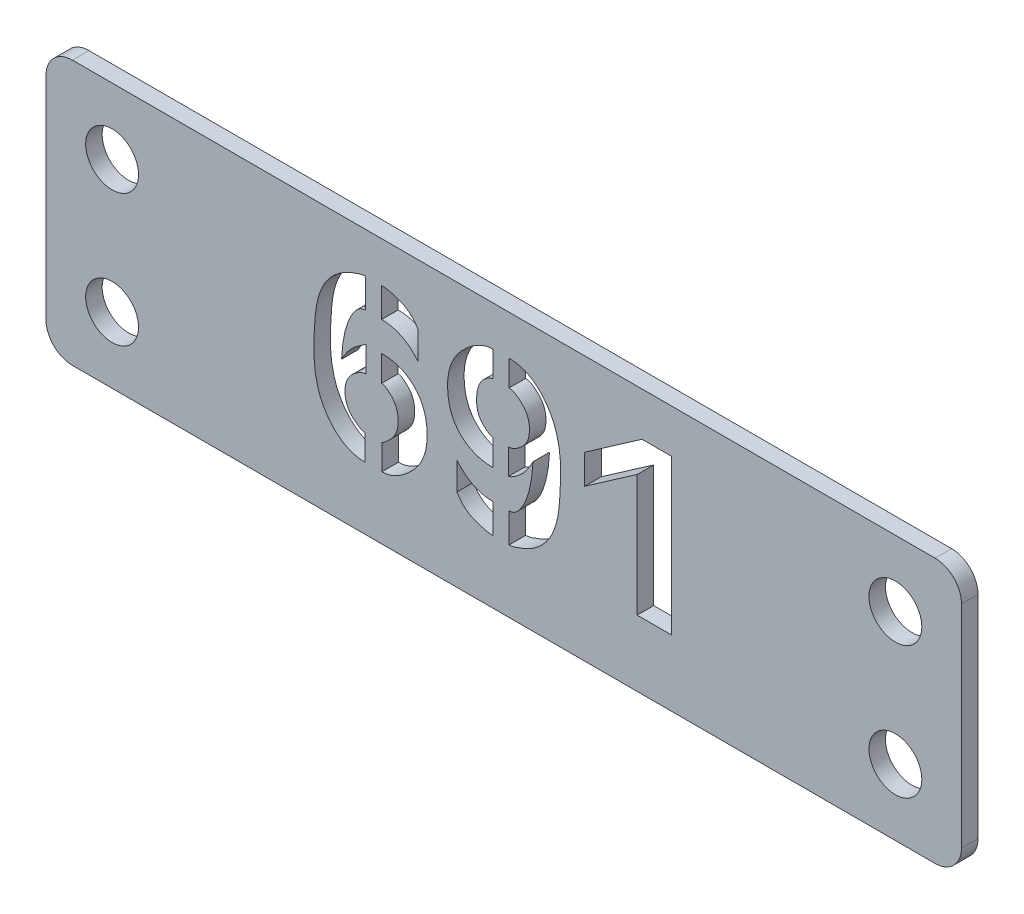
SolidWorks part; units mm, degrees
ref_plane "Front Plane" through (0, 0, 0) normal (0, 0, 1) x (1, 0, 0)
ref_plane "Top Plane" through (0, 0, 0) normal (0, 1, 0) x (1, 0, 0)
ref_plane "Right Plane" through (0, 0, 0) normal (1, 0, 0) x (0, 0, -1)
sketch "Sketch1" plane through (0, 0, 0) normal (0, 0, 1) x (1, 0, 0)
  line L1 (0, 0) -> (-87.95, 0)
  line L2 (0, 0) -> (0, 25.4)
  line L3 (0, 25.4) -> (-87.95, 25.4)
  line L4 (-87.95, 0) -> (-87.95, 25.4)
  dimension "D1" = 25.4
  dimension "D2" = 87.95
extrude "Boss-Extrude1" add sketch "Sketch1" along normal blind 1.5875
fillet "Fillet1" radius 2.54 4 edges at (-87.95, 0, 0.7937) (0, 0, 0.7937) (0, 25.4, 0.7937) (-87.95, 25.4, 0.7937)
sketch "Sketch2" plane through (0, 0, 1.5875) normal (0, 0, 1) x (1, 0, 0)
  line L0 (0, 2.54) -> (0, 22.86) construction
  line L1 (-85.41, 0) -> (-2.54, 0) construction
  line L2 (-2.54, 25.4) -> (-85.41, 25.4) construction
  line L3 (-87.95, 22.86) -> (-87.95, 2.54) construction
  circle A0 centre (-81.6, 19.05) radius 2.54
  circle A1 centre (-81.6, 6.35) radius 2.54
  circle A2 centre (-6.35, 19.05) radius 2.54
  circle A3 centre (-6.35, 6.35) radius 2.54
  dimension "D1" = 5.08
  dimension "D2" = 5.08
  dimension "D3" = 5.08
  dimension "D4" = 5.08
  dimension "D5" = 6.35
  dimension "D6" = 6.35
  dimension "D7" = 6.35
  dimension "D8" = 6.35
  dimension "D9" = 6.35
  dimension "D10" = 6.35
  dimension "D11" = 6.35
  dimension "D12" = 6.35
extrude "Cut-Extrude1" cut sketch "Sketch2" against normal blind 2.54
sketch "Sketch4" plane through (0, 0, 1.5875) normal (0, 0, 1) x (1, 0, 0)
  line L0 (-79.06, 6.35) -> (-8.89, 6.35) construction
  circle A0 centre (-81.6, 6.35) radius 2.54 construction
  circle A1 centre (-6.35, 6.35) radius 2.54 construction
  text T0 "691" font "TC_LaserSans" height in points 60
extrude "Cut-Extrude2" cut sketch "Sketch4" against normal blind 2.54
